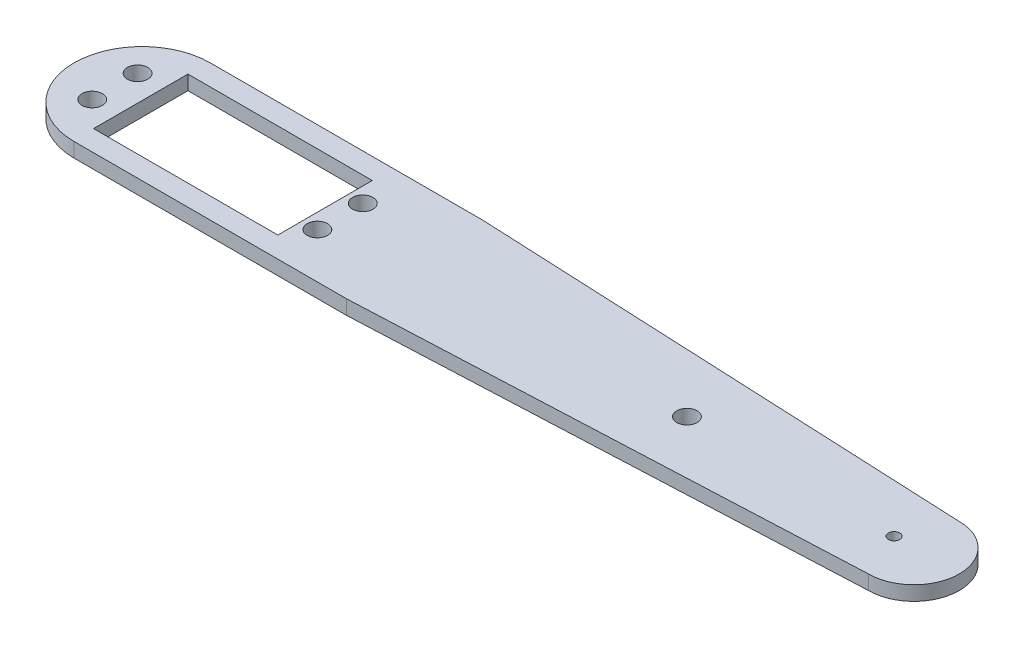
SolidWorks part; units mm, degrees
ref_plane "Front Plane" through (0, 0, 0) normal (0, 0, 1) x (1, 0, 0)
ref_plane "Top Plane" through (0, 0, 0) normal (0, 1, 0) x (1, 0, 0)
ref_plane "Right Plane" through (0, 0, 0) normal (1, 0, 0) x (0, 0, -1)
sketch "Sketch1" plane through (0, 0, 0) normal (0, 1, 0) x (1, 0, 0)
  line L0 (-162.3874, 17.2447) -> (-102.3874, 17.2447)
  line L1 (-102.3874, 17.2447) -> (7.6126, 12.2447)
  line L2 (-162.3874, -12.7553) -> (-102.3874, -12.7553)
  line L3 (-102.3874, -12.7553) -> (7.6126, -7.7553)
  line L4 (-168.3874, 19.311) -> (-168.3874, -13.0468) construction
  line L6 (-162.6926, -8.1553) -> (-122.0926, -8.1553)
  line L7 (-162.6926, -8.1553) -> (-162.6926, 12.6447)
  line L8 (-162.6926, 12.6447) -> (-122.0926, 12.6447)
  line L9 (-122.0926, -8.1553) -> (-122.0926, 12.6447)
  arc A0 (-162.3874, 17.2447) -> (-162.3874, -12.7553) centre (-162.3874, 2.2447) ccw
  arc A1 (7.6126, -7.7553) -> (7.6126, 12.2447) centre (7.6126, 2.2447) ccw
  circle A3 centre (-168.3874, 7.2447) radius 2.25
  circle A4 centre (-168.3874, -2.7553) radius 2.25
  circle A5 centre (-118.7874, 7.2447) radius 2.25
  circle A6 centre (-118.7874, -2.7553) radius 2.25
  circle A9 centre (-42.3874, 2.2447) radius 2.25
  circle A10 centre (3.2376, 2.2463) radius 1.2528
  dimension "D6" = 4.5
  dimension "D18" = 4.5
  dimension "D2" = 30
  dimension "D3" = 20
  dimension "D4" = 5
  dimension "D5" = 5
  dimension "D7" = 49.6
  dimension "D8" = 60
  dimension "D9" = 170
  dimension "D10" = 6
  dimension "D11" = 0
  dimension "D12" = 20.8
  dimension "D13" = 40.6
  dimension "D19" = 0.3053
  dimension "D14" = 10.19
  dimension "D15" = 0
  dimension "D16" = 50
extrude "Boss-Extrude1" add sketch "Sketch1" along normal blind 3.175
equation "\"D5@Sketch1\"=\"D4@Sketch1\""
